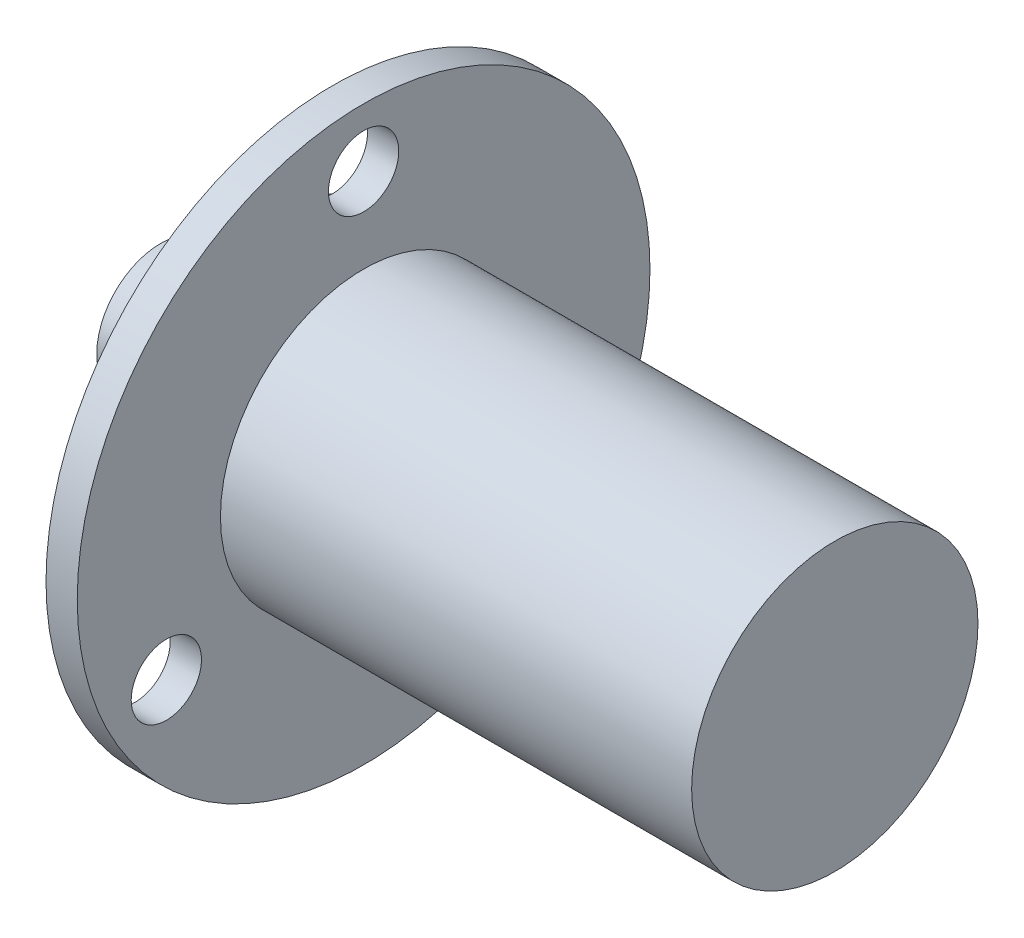
SolidWorks part; units mm, degrees
ref_plane "前视基准面" through (0, 0, 0) normal (0, 0, 1) x (1, 0, 0)
ref_plane "上视基准面" through (0, 0, 0) normal (0, 1, 0) x (1, 0, 0)
ref_plane "右视基准面" through (0, 0, 0) normal (1, 0, 0) x (0, 0, -1)
other "Configuration Table"
sketch "草图1" plane through (0, 0, 0) normal (0, 0, 1) x (1, 0, 0)
  line L0 (0, 0) -> (3303.8765, 0) construction
  line L1 (0, 0) -> (0, 4.9)
  line L2 (0, 4.9) -> (8.2, 4.9)
  line L3 (8.2, 4.9) -> (8.2, 11)
  line L4 (8.2, 11) -> (13.2, 11)
  line L5 (13.2, 11) -> (13.2, 22)
  line L6 (13.2, 22) -> (15.6, 22)
  line L7 (15.6, 22) -> (15.6, 11)
  line L8 (15.6, 11) -> (51.8, 11)
  line L9 (51.8, 11) -> (51.8, 0)
  line L10 (0, 0) -> (51.8, 0)
  dimension "D1" = 9.8
  dimension "D2" = 7.4
  dimension "D3" = 44
  dimension "D4" = 8.2
  dimension "D5" = 5
  dimension "D6" = 43.6
  dimension "D7" = 22
revolve "旋转1" add sketch "草图1" angle 360 about L0
sketch "草图2" plane through (13.2, 0, 0) normal (-1, 0, 0) x (0, 0, 1)
  circle A0 centre (0, 0) radius 17.5 construction
  circle A1 centre (0, 17.5) radius 2.7
  dimension "D1" = 5.4
  dimension "D2" = 35
extrude "切除-拉伸1" cut sketch "草图2" against normal through all both
pattern_circular "阵列(圆周)1" count 3 over 360 about axis through (0, 0, 0) along (1, 0, 0) of "切除-拉伸1"
